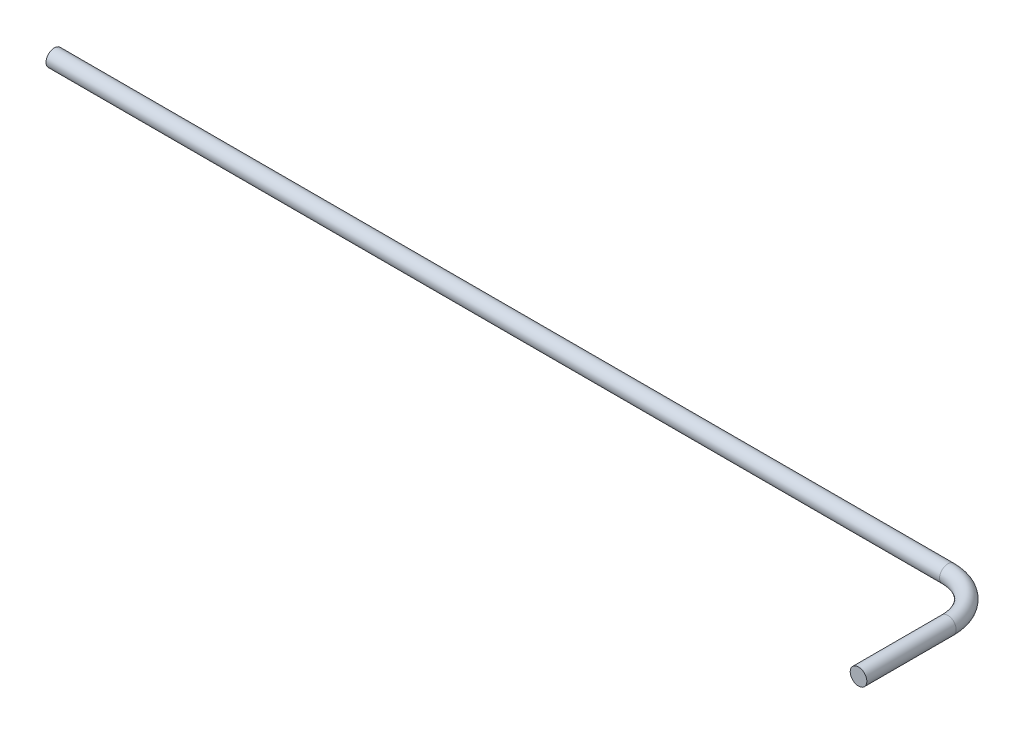
SolidWorks part; units mm, degrees
material "2024 Alloy"
ref_plane "Front Plane" through (0, 0, 0) normal (0, 0, 1) x (1, 0, 0)
ref_plane "Top Plane" through (0, 0, 0) normal (0, 1, 0) x (1, 0, 0)
ref_plane "Right Plane" through (0, 0, 0) normal (1, 0, 0) x (0, 0, -1)
sketch "Sketch1" plane through (0, 0, 0) normal (0, 0, 1) x (1, 0, 0)
  circle A0 centre (0, 0) radius 1.1811
  dimension "D1" = 2.3622
extrude "RodEnd" add sketch "Sketch1" against normal blind 12.7
sketch "Sketch2" plane through (0, 0, 0) normal (0, 0, 1) x (1, 0, 0)
  line L1 (-1.1811, -0.762) -> (1.1811, -0.762)
  line L2 (-1.1811, -0.762) -> (-1.1811, 0.762)
  line L3 (-1.1811, 0.762) -> (1.1811, 0.762)
  line L4 (1.1811, -0.762) -> (1.1811, 0.762)
  line L5 (-1.1811, -0.762) -> (1.1811, 0.762) construction
  line L6 (-1.1811, 0.762) -> (1.1811, -0.762) construction
  line L7 (-3.175, -1.1811) -> (3.175, -1.1811)
  line L8 (-3.175, -1.1811) -> (-3.175, 1.1811)
  line L9 (-3.175, 1.1811) -> (3.175, 1.1811)
  line L10 (3.175, -1.1811) -> (3.175, 1.1811)
  line L11 (-3.175, -1.1811) -> (3.175, 1.1811) construction
  line L12 (-3.175, 1.1811) -> (3.175, -1.1811) construction
  circle A0 centre (0, 0) radius 1.1811 construction
  point P0 (0, 0)
  point P8 (0, 0)
  dimension "D1" = 1.524
  dimension "D2" = 6.35
extrude "Flats" [suppressed] cut sketch "Sketch2" against normal blind 5.715
sketch "Sketch3" [suppressed] plane through (0, 0.762, 0) normal (0, 1, 0) x (1, 0, 0)
  line L0 (0.968, 0) -> (-0.968, 0) construction
  circle A0 centre (0, 1.27) radius 0.5715
  dimension "D2" = 1.143
  dimension "D1" = 1.27
extrude "Hole" [suppressed] cut sketch "Sketch3" against normal through all
sketch "Sketch4" plane through (0, 0, -12.7) normal (0, 0, -1) x (-1, 0, 0)
  line L0 (6.35, 0) -> (6.35, 2.0828) construction
  circle A0 centre (0, 0) radius 1.1811
  circle A1 centre (0, 0) radius 1.1811 construction
  dimension "D1" = 6.35
revolve "Revolve1" add sketch "Sketch4" angle 90 about L0
sketch "Sketch5" plane through (-6.35, 0, 0) normal (-1, 0, 0) x (0, 0, 1)
  circle A0 centre (-19.05, 0) radius 1.1811
  circle A1 centre (-19.05, 0) radius 1.1811 construction
extrude "Boss-Extrude1" add sketch "Sketch5" along normal blind 127
